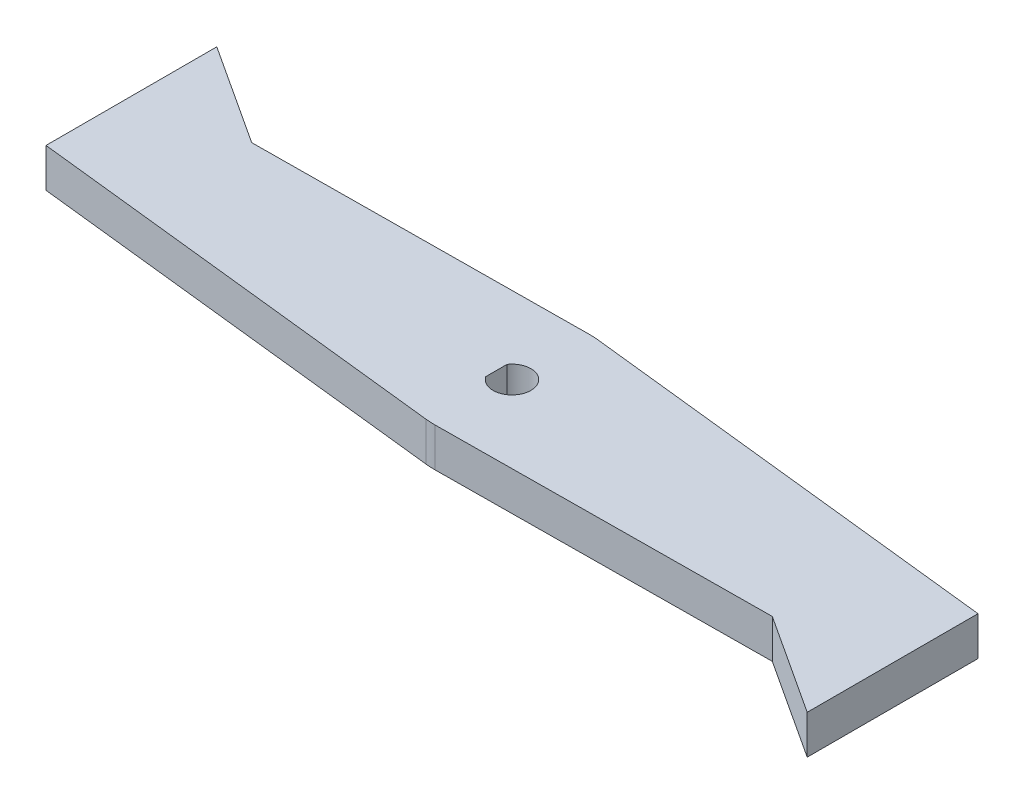
SolidWorks part; units mm, degrees
ref_plane "Front Plane" through (0, 0, 0) normal (0, 0, 1) x (1, 0, 0)
ref_plane "Top Plane" through (0, 0, 0) normal (0, 1, 0) x (1, 0, 0)
ref_plane "Right Plane" through (0, 0, 0) normal (1, 0, 0) x (0, 0, -1)
sketch "Sketch1" plane through (0, 0, 0) normal (0, 1, 0) x (1, 0, 0)
  line L0 (-2.4257, 1.6948) -> (-2.4257, -1.6948) construction
  line L1 (2.9591, 2.0342) -> (2.9591, -4.2641) construction
  line L2 (-2.5527, 1.7343) -> (-2.5527, -1.7343)
  line L3 (71.12, 4.9353) -> (71.12, -22.9389)
  line L4 (71.12, 4.9353) -> (1.3919, 12.6235)
  line L5 (71.12, -22.9389) -> (54.7258, -12.2427)
  line L6 (54.7258, -12.2427) -> (0.1062, -12.6996)
  line L7 (-71.12, -4.9353) -> (-1.3919, -12.6235)
  line L8 (-71.12, -4.9353) -> (-71.12, 22.9389)
  line L9 (-71.12, 22.9389) -> (-54.7258, 12.2427)
  line L10 (-54.7258, 12.2427) -> (-0.1062, 12.6996)
  arc A0 (-2.4257, -1.6948) -> (-2.4257, 1.6948) centre (0, 0) ccw construction
  arc A1 (-2.5527, -1.7343) -> (-2.5527, 1.7343) centre (0, 0) ccw
  arc A2 (-1.3919, -12.6235) -> (0.1062, -12.6996) centre (0, 0) ccw
  arc A3 (1.3919, 12.6235) -> (-0.1062, 12.6996) centre (0, 0) ccw
  point P22 (0, 0)
  dimension "D1" = 5.9182
  dimension "D4" = 25.4
  dimension "D2" = 5.3848
  dimension "D5" = 71.12
  dimension "D3" = 0.127
  dimension "D6" = 2
extrude "Boss-Extrude1" add sketch "Sketch1" along normal blind 6.35
